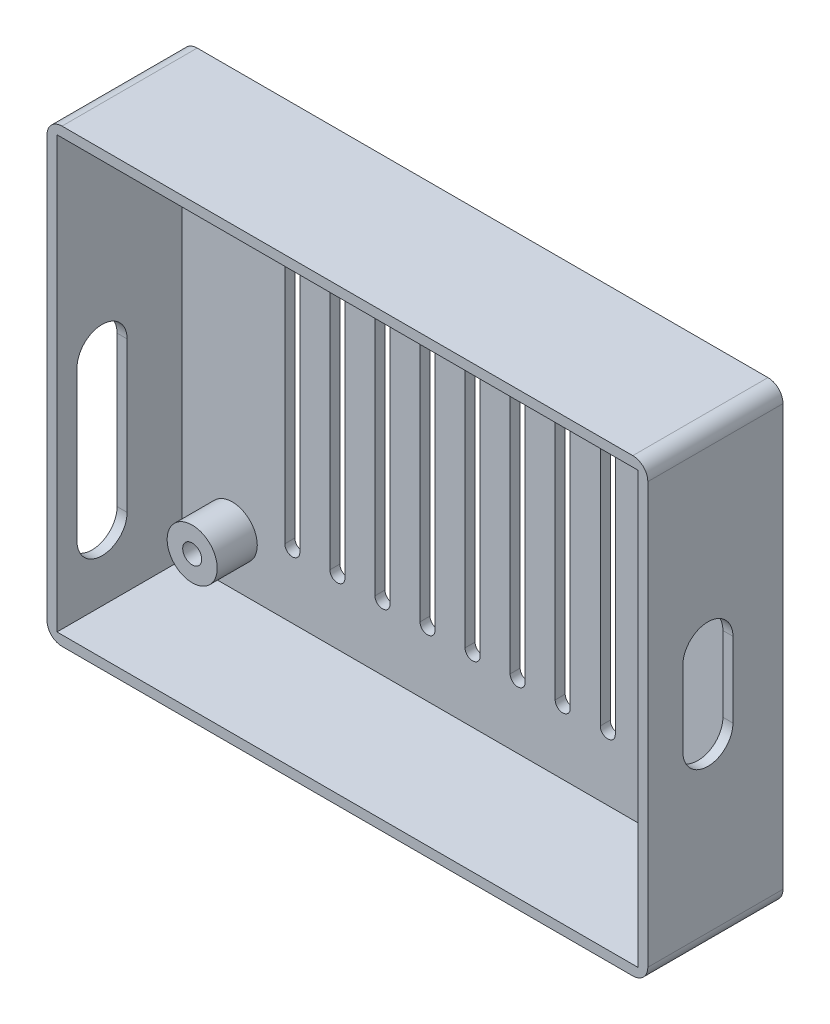
SolidWorks part; units mm, degrees
material "ABS"
ref_plane "Plan de face" through (0, 0, 0) normal (0, 0, 1) x (1, 0, 0)
ref_plane "Plan de dessus" through (0, 0, 0) normal (0, 1, 0) x (1, 0, 0)
ref_plane "Plan de droite" through (0, 0, 0) normal (1, 0, 0) x (0, 0, -1)
sketch "Esquisse2" plane through (0, 0, 0) normal (0, 0, 1) x (1, 0, 0)
  line L1 (60, -45) -> (-60, -45)
  line L2 (60, -45) -> (60, 45)
  line L3 (60, 45) -> (-60, 45)
  line L4 (-60, -45) -> (-60, 45)
  line L5 (60, -45) -> (-60, 45) construction
  line L6 (60, 45) -> (-60, -45) construction
  point P0 (0, 0)
  dimension "D1" = 120
  dimension "D2" = 90
extrude "Boss.-Extru.1" add sketch "Esquisse2" along normal blind 2
sketch "Esquisse3" plane through (0, 0, 2) normal (0, 0, 1) x (1, 0, 0)
  line L1 (48, -33) -> (-48, -33) construction
  line L2 (48, -33) -> (48, 33) construction
  line L3 (48, 33) -> (-48, 33) construction
  line L4 (-48, -33) -> (-48, 33) construction
  line L5 (48, -33) -> (-48, 33) construction
  line L6 (48, 33) -> (-48, -33) construction
  circle A0 centre (-48, 33) radius 5
  circle A1 centre (48, 33) radius 5
  circle A2 centre (48, -33) radius 5
  circle A3 centre (-48, -33) radius 5
  point P8 (0, 0)
  dimension "D7" = 10
  dimension "D8" = 10
  dimension "D9" = 10
  dimension "D10" = 10
  dimension "D1" = 96
  dimension "D2" = 66
  dimension "D3" = 96
  dimension "D4" = 66
  dimension "D5" = 33
  dimension "D6" = 0
extrude "Boss.-Extru.2" add sketch "Esquisse3" along normal blind 8
hole_wizard "Chambrage pour vis à tête ronde bombée #61" positions "Esquisse4" profile "Esquisse6" counterbore size "#6" standard "Ansi Inch" end condition through all
sketch "Esquisse4" plane through (0, 0, 0) normal (0, 0, -1) x (-1, 0, 0)
  point P0 (48, -33)
  dimension "D1" = 48
  dimension "D2" = 33
sketch "Esquisse6" plane through (-48, -33, 0) normal (1, 0, 0) x (0, 1, 0)
  line L0 (0, 0) -> (0, 10)
  line L1 (0, 10) -> (1.8986, 10)
  line L3 (1.8986, 10) -> (1.8986, 2.4638)
  line L4 (1.8986, 2.4638) -> (3.7706, 2.4638)
  line L5 (3.7706, 2.4638) -> (3.7706, 0)
  line L7 (3.7706, 0) -> (0, 0)
  line L11 (0, -6.35) -> (0, 107.95) construction
  dimension "Diamètre du perçage jusqu'au prochain" = 3.7973
  dimension "Profondeur du perçage jusqu'au prochain" = 10
  dimension "Diamètre du chambrage" = 7.5413
  dimension "Profondeur du chambrage" = 2.4638
pattern_linear "Répétition linéaire1" count 2 spacing 96 along (1, 0, 0) count 2 spacing 66 along (0, 1, 0) of "Chambrage pour vis à tête ronde bombée #61"
sketch "Esquisse7" plane through (0, 0, 2) normal (0, 0, 1) x (1, 0, 0)
  line L0 (0, -30) -> (0, 30) construction
  line L1 (-1.5, -30) -> (-1.5, 30)
  line L2 (1.5, -30) -> (1.5, 30)
  arc A0 (-1.5, -30) -> (1.5, -30) centre (0, -30) ccw
  arc A1 (1.5, 30) -> (-1.5, 30) centre (0, 30) ccw
  point P2 (0, 0)
  dimension "D1" = 3
  dimension "D2" = 60
extrude "Enlèv. mat.-Extru.1" cut sketch "Esquisse7" against normal blind 8
pattern_linear "Répétition linéaire2" count 5 spacing 9 along (-1, 0, 0) count 5 spacing 9 along (1, 0, 0) of "Enlèv. mat.-Extru.1"
sketch "Esquisse8" plane through (0, 0, 2) normal (0, 0, 1) x (1, 0, 0)
  line L5 (-58, 43) -> (58, -43) construction
  line L6 (-58, -43) -> (58, 43) construction
  line L7 (-60, 45) -> (60, 45)
  line L8 (-60, 45) -> (-60, -45)
  line L9 (-60, -45) -> (60, -45)
  line L10 (60, 45) -> (60, -45)
  line L11 (-60, 45) -> (60, -45) construction
  line L12 (-60, -45) -> (60, 45) construction
  line L13 (58, -43) -> (-58, -43)
  line L14 (58, -43) -> (58, 43)
  line L15 (58, 43) -> (-58, 43)
  line L16 (-58, -43) -> (-58, 43)
  line L17 (58, -43) -> (-58, 43) construction
  line L18 (58, 43) -> (-58, -43) construction
  point P0 (0, 0)
  point P6 (0, 0)
  point P12 (0, 0)
  point P13 (0, 0)
  point P14 (0, 0)
  point P15 (0, 0)
  point P16 (0, 0)
  point P17 (0, 0)
  point P18 (0, 0)
  dimension "D1" = 2
  dimension "D2" = 2
extrude "Boss.-Extru.3" add sketch "Esquisse8" along normal blind 25 contours L16 L15 L14 L13 | L8 L9 L10 L7
sketch "Esquisse9" plane through (-60, 0, 0) normal (-1, 0, 0) x (0, 0, 1)
  line L0 (18, 0.6892) -> (18, -29.3108) construction
  line L1 (23, 0.6892) -> (23, -29.3108)
  line L2 (13, 0.6892) -> (13, -29.3108)
  line L3 (0, 45) -> (0, -45) construction
  arc A0 (23, 0.6892) -> (13, 0.6892) centre (18, 0.6892) ccw
  arc A1 (13, -29.3108) -> (23, -29.3108) centre (18, -29.3108) ccw
  point P2 (18, -14.3108)
  point P7 (0, 0)
  point P8 (9.9445, -10.972)
  point P9 (14.4951, -11.4999)
  point P10 (16.1874, -11.487)
  point P13 (18, -14.3108)
  dimension "D1" = 10
  dimension "D2" = 30
  dimension "D3" = 18
extrude "Enlèv. mat.-Extru.2" cut sketch "Esquisse9" against normal up to next
sketch "Esquisse10" plane through (60, 0, 0) normal (1, 0, 0) x (0, 0, -1)
  line L0 (-15, -8.2495) -> (-15, 6.7505) construction
  line L1 (-20, -8.2495) -> (-20, 6.7505)
  line L2 (-10, -8.2495) -> (-10, 6.7505)
  line L3 (0, -45) -> (0, 45) construction
  arc A0 (-20, -8.2495) -> (-10, -8.2495) centre (-15, -8.2495) ccw
  arc A1 (-10, 6.7505) -> (-20, 6.7505) centre (-15, 6.7505) ccw
  point P2 (-15, -0.7495)
  point P7 (-11.8049, 4.5109)
  point P8 (-11.883, -4.5995)
  point P9 (-11.6705, 1.3596)
  point P10 (-12.0588, -0.6251)
  point P11 (-13.6008, -0.7495)
  dimension "D1" = 15
  dimension "D2" = 10
  dimension "D3" = 15
extrude "Enlèv. mat.-Extru.3" cut sketch "Esquisse10" against normal blind 2
fillet "Congé1" radius 3 4 edges at (60, 45, 13.5) (60, -45, 13.5) (-60, 45, 13.5) (-60, -45, 13.5)
